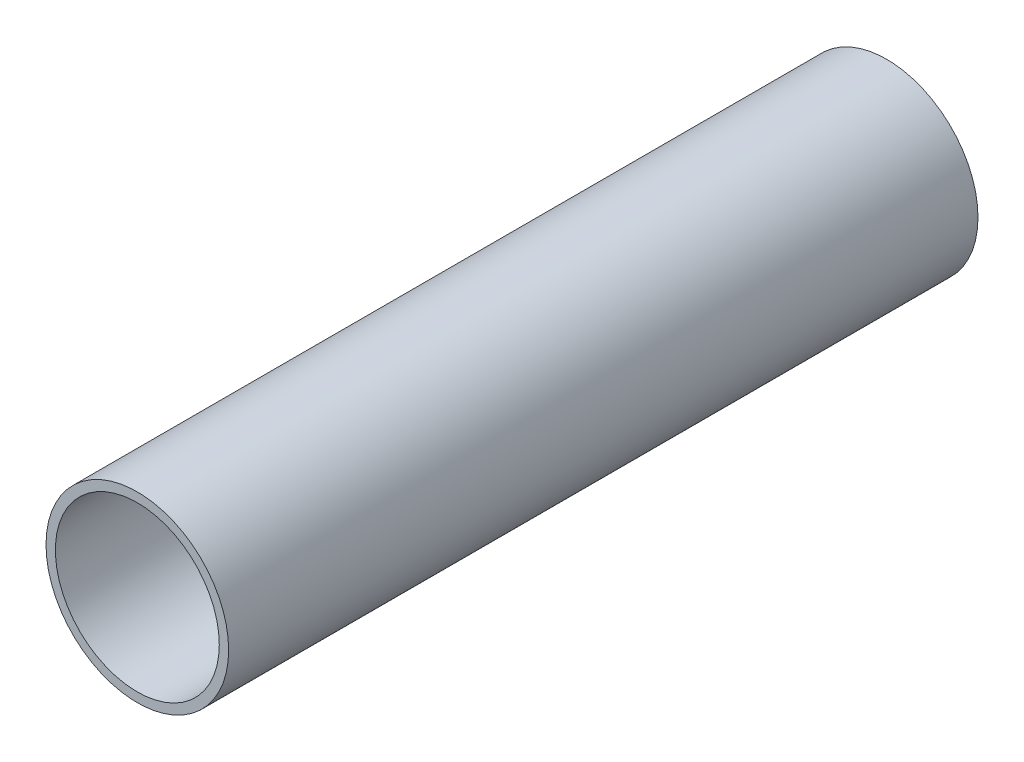
SolidWorks part; units mm, degrees
ref_plane "Front Plane" through (0, 0, 0) normal (0, 0, 1) x (1, 0, 0)
ref_plane "Top Plane" through (0, 0, 0) normal (0, 1, 0) x (1, 0, 0)
ref_plane "Right Plane" through (0, 0, 0) normal (1, 0, 0) x (0, 0, -1)
sketch "Sketch1" plane through (0, 0, 0) normal (0, 0, 1) x (1, 0, 0)
  circle A0 centre (0, 0) radius 1.75
  circle A1 centre (0, 0) radius 1.95
  dimension "D1" = 3.9
  dimension "D2" = 0.2
extrude "Boss-Extrude1" add sketch "Sketch1" along normal blind 16
